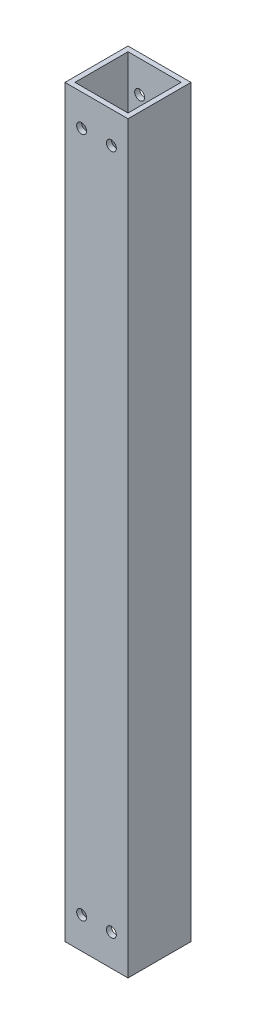
SolidWorks part; units mm, degrees
material "1060 Alloy"
ref_plane "Front Plane" through (0, 0, 0) normal (0, 0, 1) x (1, 0, 0)
ref_plane "Top Plane" through (0, 0, 0) normal (0, 1, 0) x (1, 0, 0)
ref_plane "Right Plane" through (0, 0, 0) normal (1, 0, 0) x (0, 0, -1)
sketch "Sketch1" plane through (0, 0, 0) normal (0, 1, 0) x (1, 0, 0)
  line L0 (-10.7, -10.7) -> (-10.7, 10.7)
  line L1 (12.7, -12.7) -> (-12.7, -12.7)
  line L2 (12.7, -12.7) -> (12.7, 12.7)
  line L3 (12.7, 12.7) -> (-12.7, 12.7)
  line L4 (-12.7, -12.7) -> (-12.7, 12.7)
  line L5 (12.7, -12.7) -> (-12.7, 12.7) construction
  line L6 (12.7, 12.7) -> (-12.7, -12.7) construction
  line L7 (10.7, 10.7) -> (-10.7, 10.7)
  line L8 (10.7, -10.7) -> (10.7, 10.7)
  line L9 (10.7, -10.7) -> (-10.7, -10.7)
  point P0 (0, 0)
  dimension "D1" = 2
extrude "Boss-Extrude1" add sketch "Sketch1" along normal blind 300
sketch "Sketch2" plane through (0, 0, 12.7) normal (0, 0, 1) x (1, 0, 0)
  circle A2 centre (-6, 12.7) radius 2
  circle A3 centre (6, 12.7) radius 2
  circle A4 centre (6, 287.3) radius 2
  circle A5 centre (-6, 287.3) radius 2
extrude "Cut-Extrude1" cut sketch "Sketch2" against normal through all both and the other way through all
